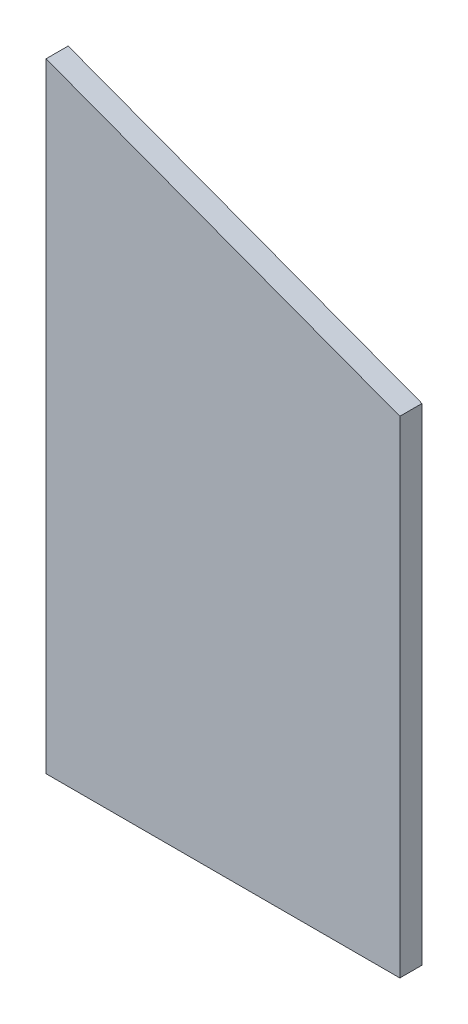
SolidWorks part; units mm, degrees
ref_plane "Front Plane" through (0, 0, 0) normal (0, 0, 1) x (1, 0, 0)
ref_plane "Top Plane" through (0, 0, 0) normal (0, 1, 0) x (1, 0, 0)
ref_plane "Right Plane" through (0, 0, 0) normal (1, 0, 0) x (0, 0, -1)
sketch "Sketch1" plane through (0, 0, 0) normal (0, 0, 1) x (1, 0, 0)
  line L0 (0, 0) -> (0, 177.8)
  line L1 (0, 177.8) -> (101.6, 139.7)
  line L2 (101.6, 139.7) -> (101.6, 0)
  line L3 (101.6, 0) -> (0, 0)
  dimension "D1" = 177.8
  dimension "D2" = 139.7
  dimension "D3" = 101.6
extrude "Boss-Extrude1" add sketch "Sketch1" along normal blind 6.35
